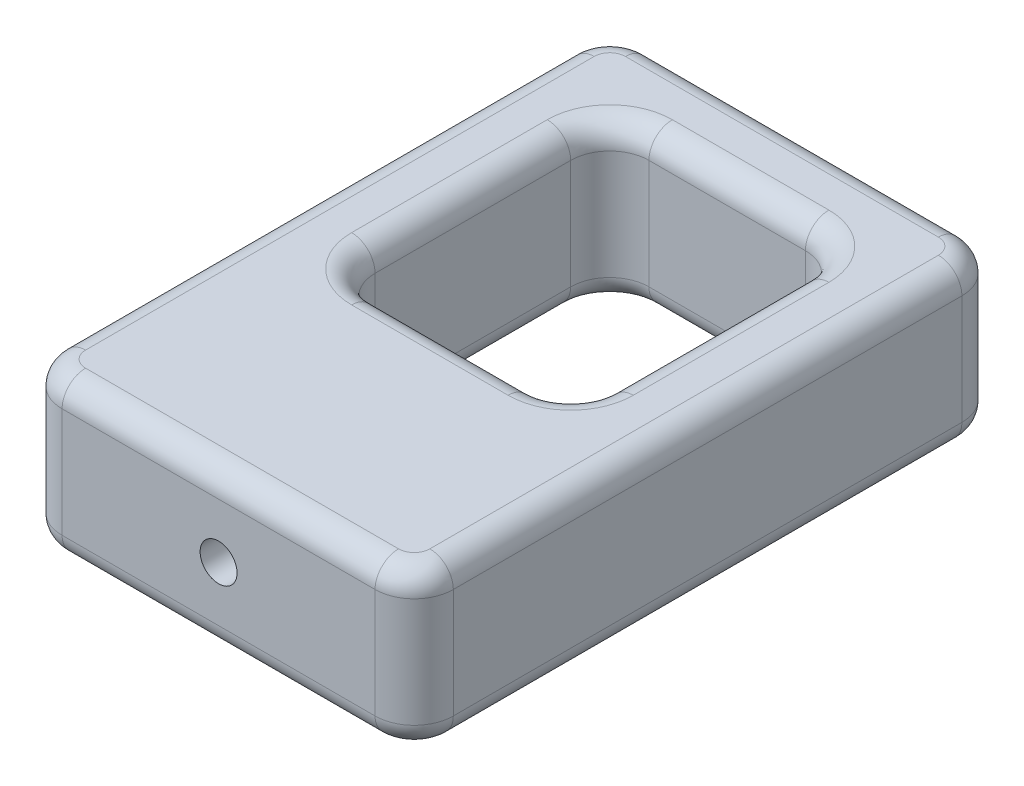
SolidWorks part; units mm, degrees
ref_plane "Front Plane" through (0, 0, 0) normal (0, 0, 1) x (1, 0, 0)
ref_plane "Top Plane" through (0, 0, 0) normal (0, 1, 0) x (1, 0, 0)
ref_plane "Right Plane" through (0, 0, 0) normal (1, 0, 0) x (0, 0, -1)
sketch "Sketch1" plane through (0, 0, 0) normal (0, 1, 0) x (1, 0, 0)
  line L1 (-6.35, 9.525) -> (6.35, 9.525)
  line L2 (-6.35, 9.525) -> (-6.35, -9.525)
  line L3 (-6.35, -9.525) -> (6.35, -9.525)
  line L4 (6.35, 9.525) -> (6.35, -9.525)
  line L5 (-6.35, 9.525) -> (6.35, -9.525) construction
  line L6 (-6.35, -9.525) -> (6.35, 9.525) construction
  point P0 (0, 0)
  dimension "D1" = 12.7
  dimension "D2" = 19.05
extrude "Boss-Extrude1" add sketch "Sketch1" along normal blind 5.08
sketch "Sketch2" plane through (0, 0, 0) normal (0, -1, 0) x (1, 0, 0)
  line L0 (6.35, -9.525) -> (-6.35, -9.525) construction
  line L1 (-3.81, -6.985) -> (3.81, -6.985)
  line L2 (-3.81, -6.985) -> (-3.81, 1.905)
  line L3 (-3.81, 1.905) -> (3.81, 1.905)
  line L4 (3.81, -6.985) -> (3.81, 1.905)
  line L5 (-3.81, -6.985) -> (3.81, 1.905) construction
  line L6 (-3.81, 1.905) -> (3.81, -6.985) construction
  line L7 (6.35, 9.525) -> (6.35, -9.525) construction
  line L8 (-6.35, -9.525) -> (-6.35, 9.525) construction
  line L9 (-6.35, 9.525) -> (6.35, 9.525) construction
  point P0 (0, -2.54)
  dimension "D1" = 2.54
  dimension "D2" = 2.54
  dimension "D3" = 2.54
  dimension "D4" = 7.62
extrude "Cut-Extrude1" cut sketch "Sketch2" against normal through all
sketch "Sketch3" plane through (0, 0, 9.525) normal (0, 0, 1) x (1, 0, 0)
  line L0 (0, 0) -> (0, 5.08) construction
  line L1 (-6.35, 5.08) -> (6.35, 5.08) construction
  line L2 (6.35, 2.54) -> (-6.35, 2.54) construction
  line L3 (6.35, 5.08) -> (6.35, 0) construction
  line L4 (-6.35, 5.08) -> (-6.35, 0) construction
  circle A0 centre (0, 2.54) radius 0.6
extrude "Cut-Extrude3" cut sketch "Sketch3" against normal blind 7.62
fillet "Fillet1" radius 1.27 4 edges at (6.35, 2.54, -9.525) (-6.35, 2.54, -9.525) (-6.35, 2.54, 9.525) (6.35, 2.54, 9.525)
fillet "Fillet2" radius 1.27 4 edges at (-3.81, 2.54, -6.985) (3.81, 2.54, -6.985) (-3.81, 2.54, 1.905) (3.81, 2.54, 1.905)
fillet "Fillet3" radius 0.762 8 edges at (5.978, 5.08, 9.153) (0, 5.08, 9.525) (-5.978, 5.08, 9.153) (-6.35, 5.08, 0) (-5.978, 5.08, -9.153) (0, 5.08, -9.525) (5.978, 5.08, -9.153) (6.35, 5.08, 0)
fillet "Fillet4" radius 0.762 24 edges at (3.438, 5.08, 1.533) (3.81, 5.08, -2.54) (3.438, 5.08, -6.613) (0, 5.08, -6.985) (-3.438, 5.08, -6.613) (-3.81, 5.08, -2.54) (-3.438, 5.08, 1.533) (3.438, 0, 1.533) (3.81, 0, -2.54) (3.438, 0, -6.613) (0, 0, -6.985) (-3.438, 0, -6.613) (-3.81, 0, -2.54) (-3.438, 0, 1.533) (-5.978, 0, -9.153) (0, 0, -9.525) (5.978, 0, -9.153) (6.35, 0, 0) (5.978, 0, 9.153) (0, 0, 9.525) (-5.978, 0, 9.153) (0, 5.08, 1.905) (0, 0, 1.905) (-6.35, 0, 0)
equation "\"D3@Sketch2\"=\"D2@Sketch2\""
